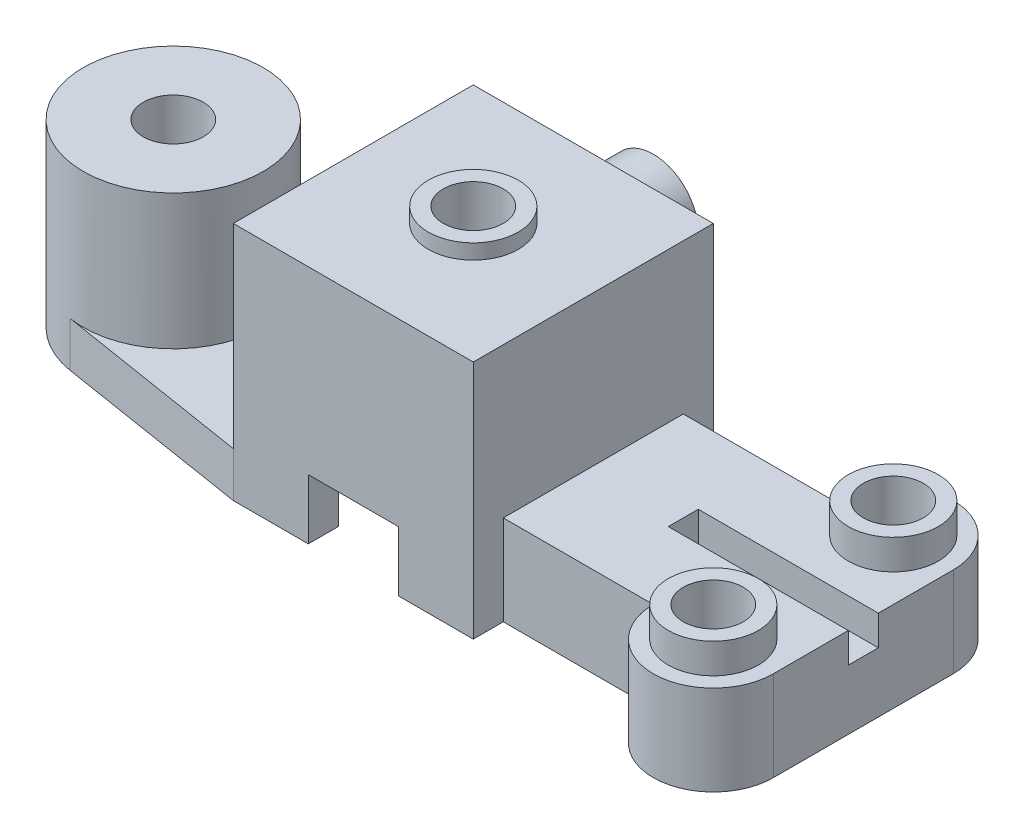
SolidWorks part; units mm, degrees
ref_plane "Front Plane" through (0, 0, 0) normal (0, 0, 1) x (1, 0, 0)
ref_plane "Top Plane" through (0, 0, 0) normal (0, 1, 0) x (1, 0, 0)
ref_plane "Right Plane" through (0, 0, 0) normal (1, 0, 0) x (0, 0, -1)
sketch "Sketch1" plane through (0, 0, 0) normal (0, 1, 0) x (1, 0, 0)
  line L1 (-40, 40) -> (40, 40)
  line L2 (-40, 40) -> (-40, -40)
  line L3 (-40, -40) -> (40, -40)
  line L4 (40, 40) -> (40, -40)
  line L5 (-40, 40) -> (40, -40) construction
  line L6 (-40, -40) -> (40, 40) construction
  point P0 (0, 0)
  dimension "D1" = 80
  dimension "D2" = 80
extrude "Boss-Extrude1" add sketch "Sketch1" along normal blind 80
sketch "Sketch2" plane through (0, 0, 0) normal (0, -1, 0) x (1, 0, 0)
  line L9 (30, -30) -> (30, 30)
  line L10 (30, 30) -> (-30, 30)
  line L11 (-30, 30) -> (-30, -30)
  line L12 (-30, -30) -> (30, -30)
  line L13 (30, -30) -> (30, 30)
  line L14 (30, 30) -> (-30, 30)
  line L15 (-30, 30) -> (-30, -30)
  line L16 (-30, -30) -> (30, -30)
  dimension "D1" = 10
extrude "Cut-Extrude1" cut sketch "Sketch2" against normal blind 70 and the other way through all
sketch "Sketch3" plane through (0, 80, 0) normal (0, 1, 0) x (1, 0, 0)
  circle A0 centre (0, 0) radius 15
  circle A1 centre (0, 0) radius 10
  dimension "D1" = 30
  dimension "D2" = 20
extrude "Boss-Extrude2" add sketch "Sketch3" along normal blind 5
sketch "Sketch4" plane through (0, 0, 0) normal (0, 1, 0) x (1, 0, 0)
  line L0 (40, 30) -> (90, 30)
  line L1 (40, -40) -> (40, 40) construction
  line L2 (0, 0) -> (69.516, 0) construction
  line L3 (40, -30) -> (90, -30)
  line L4 (40, -30) -> (40, 30)
  line L5 (130, 30) -> (130, -30)
  line L6 (40, 40) -> (-40, 40) construction
  line L7 (-40, -40) -> (40, -40) construction
  arc A0 (130, 30) -> (90, 30) centre (110, 30) ccw
  arc A1 (130, -30) -> (90, -30) centre (110, -30) cw
  point P9 (0, 0)
  point P17 (74.7489, 30)
  dimension "D1" = 40
  dimension "D2" = 60
  dimension "D3" = 80
  dimension "D4" = 110
  dimension "D5" = 60
extrude "Boss-Extrude3" add sketch "Sketch4" along normal blind 30 contours L3 A1 L5 A0 L0 L4
sketch "Sketch5" plane through (0, 30, 0) normal (0, 1, 0) x (1, 0, 0)
  circle A0 centre (110, 30) radius 15
  circle A2 centre (110, -30) radius 15
  point P3 (-98.1329, 24.1608)
  dimension "D1" = 30
extrude "Boss-Extrude4" add sketch "Sketch5" along normal blind 10
hole_wizard "Hole1" positions "Sketch6" profile "Sketch7" legacy end condition through all
sketch "Sketch6" plane through (0, 40, 0) normal (0, 1, 0) x (1, 0, 0)
  point P0 (110, 30)
  point P3 (110, -30)
sketch "Sketch7" plane through (110, 40, -30) normal (1, 0, 0) x (0, 0, 1)
  line L0 (0, 0) -> (0, 40)
  line L1 (0, 40) -> (5, 40)
  line L2 (5, 40) -> (5, 15)
  line L3 (5, 15) -> (10, 15)
  line L4 (10, 15) -> (10, 0)
  line L5 (10, 0) -> (0, 0)
  line L6 (0, 110) -> (0, -10) construction
  dimension "Diameter" = 10
  dimension "Depth" = 40
  dimension "C-Bore Diameter" = 20
  dimension "C-Bore Depth" = 15
sketch "Sketch8" plane through (0, 30, 0) normal (0, 1, 0) x (1, 0, 0)
  line L0 (0, 0) -> (163.0857, 0) construction
  line L1 (70, 5) -> (130, 5)
  line L2 (70, 5) -> (70, -5)
  line L3 (70, -5) -> (130, -5)
  line L4 (130, 5) -> (130, -5)
  line L5 (130, 30) -> (130, -30) construction
  dimension "D1" = 60
  dimension "D2" = 10
extrude "Cut-Extrude2" cut sketch "Sketch8" against normal blind 10
sketch "Sketch9" plane through (0, 0, 0) normal (0, 1, 0) x (1, 0, 0)
  line L0 (0, 0) -> (-100, 0) construction
  circle A0 centre (-100, 0) radius 30
  dimension "D1" = 60
  dimension "D2" = 100
extrude "Boss-Extrude5" add sketch "Sketch9" along normal blind 60 separate body
sketch "Sketch10" plane through (0, 0, 0) normal (0, 1, 0) x (1, 0, 0)
  line L0 (-40, 40) -> (-40, -40) construction
  line L1 (-40, 40) -> (-40, -40)
  line L2 (-104.7479, 29.6219) -> (-40, 40)
  line L3 (-104.7479, -29.6219) -> (-40, -40)
  circle A0 centre (-100, 0) radius 30 construction
  arc A1 (-104.7479, -29.6219) -> (-104.7479, 29.6219) centre (-100, 0) ccw
extrude "Boss-Extrude6" add sketch "Sketch10" along normal blind 15
sketch "Sketch11" plane through (0, 0, -40) normal (0, 0, -1) x (-1, 0, 0)
  line L0 (-40, 0) -> (40, 0) construction
  line L1 (-15, 20) -> (15, 20)
  line L2 (-15, 20) -> (-15, 0)
  line L3 (-15, 0) -> (15, 0)
  line L4 (15, 20) -> (15, 0)
  line L5 (-15, 20) -> (15, 0) construction
  line L6 (-15, 0) -> (15, 20) construction
  line L7 (0, 0) -> (0, 10) construction
  point P0 (0, 10)
  dimension "D1" = 30
  dimension "D2" = 20
extrude "Cut-Extrude3" cut sketch "Sketch11" against normal through all
sketch "Sketch12" plane through (0, 0, -40) normal (0, 0, -1) x (-1, 0, 0)
  circle A0 centre (0, 55) radius 15
  point P2 (0, 0)
  dimension "D1" = 30
  dimension "D2" = 55
extrude "Boss-Extrude7" add sketch "Sketch12" along normal blind 20
hole_wizard "Hole2" positions "Sketch13" profile "Sketch14" legacy end condition through all
sketch "Sketch13" plane through (0, 80, 0) normal (0, 1, 0) x (1, 0, 0)
  point P0 (0, 0)
sketch "Sketch14" plane through (0, 80, 0) normal (1, 0, 0) x (0, 0, 1)
  line L0 (0, 0) -> (0, 80)
  line L1 (0, 80) -> (10, 80)
  line L2 (10, 80) -> (10, 0)
  line L3 (10, 0) -> (0, 0)
  line L4 (0, 110) -> (0, -10) construction
  dimension "Diameter" = 20
  dimension "Depth" = 80
hole_wizard "Hole3" positions "Sketch15" profile "Sketch16" legacy
sketch "Sketch15" plane through (0, 0, -60) normal (0, 0, -1) x (-1, 0, 0)
  point P0 (0, 55)
sketch "Sketch16" plane through (0, 55, -60) normal (1, 0, 0) x (0, 1, 0)
  line L0 (0, 0) -> (0, 30)
  line L1 (0, 30) -> (10, 30)
  line L2 (10, 30) -> (10, 0)
  line L3 (10, 0) -> (0, 0)
  line L4 (0, 110) -> (0, -10) construction
  dimension "Diameter" = 20
  dimension "Depth" = 30
hole_wizard "Hole4" positions "Sketch17" profile "Sketch18" legacy end condition up to next
sketch "Sketch17" plane through (0, 60, 0) normal (0, 1, 0) x (1, 0, 0)
  point P0 (-100, 0)
sketch "Sketch18" plane through (-100, 60, 0) normal (1, 0, 0) x (0, 0, 1)
  line L0 (0, 0) -> (0, 60)
  line L1 (0, 60) -> (10, 60)
  line L2 (10, 60) -> (10, 0)
  line L3 (10, 0) -> (0, 0)
  line L4 (0, 110) -> (0, -10) construction
  dimension "Diameter" = 20
  dimension "Depth" = 60
